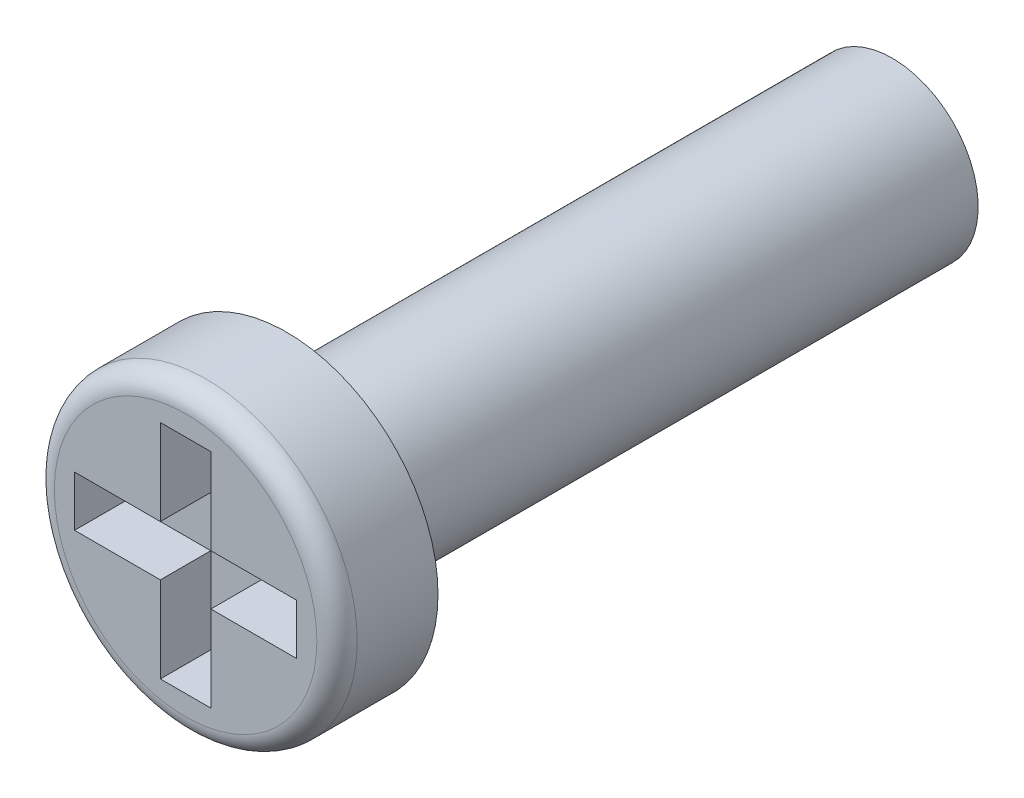
SolidWorks part; units mm, degrees
ref_plane "Front Plane" through (0, 0, 0) normal (0, 0, 1) x (1, 0, 0)
ref_plane "Top Plane" through (0, 0, 0) normal (0, 1, 0) x (1, 0, 0)
ref_plane "Right Plane" through (0, 0, 0) normal (1, 0, 0) x (0, 0, -1)
sketch "Sketch1" plane through (0, 0, 0) normal (0, 0, 1) x (1, 0, 0)
  circle A0 centre (0, 0) radius 1.5
  dimension "D1" = 3
extrude "Boss-Extrude1" add sketch "Sketch1" along normal blind 1
sketch "Sketch2" plane through (0, 0, 0) normal (0, 0, -1) x (-1, 0, 0)
  circle A0 centre (0, 0) radius 0.85
  dimension "D1" = 1.7
extrude "Boss-Extrude2" add sketch "Sketch2" along normal blind 6
sketch "Sketch3" plane through (0, 0, 1) normal (0, 0, 1) x (1, 0, 0)
  line L0 (-0.25, 1.1) -> (-0.25, 0.25)
  line L1 (-0.25, 1.1) -> (0.25, 1.1)
  line L3 (-0.25, -1.1) -> (0.25, -1.1)
  line L5 (0, -1.1) -> (0, 1.1) construction
  line L6 (-0.25, 0) -> (0.25, 0) construction
  line L8 (-1.1, 0.25) -> (-1.1, -0.25)
  line L10 (1.1, 0.25) -> (1.1, -0.25)
  line L11 (0, -0.25) -> (0, 0.25) construction
  line L12 (-1.1, 0) -> (1.1, 0) construction
  line L13 (-0.25, -1.1) -> (-0.25, -0.25)
  line L14 (0.25, 1.1) -> (0.25, 0.25)
  line L15 (0.25, -1.1) -> (0.25, -0.25)
  line L16 (-1.1, 0.25) -> (-0.25, 0.25)
  line L17 (0.25, 0.25) -> (1.1, 0.25)
  line L18 (-1.1, -0.25) -> (-0.25, -0.25)
  line L19 (0.25, -0.25) -> (1.1, -0.25)
  point P0 (0, 0)
  point P4 (0, 0)
  dimension "D1" = 2.2
  dimension "D2" = 0.5
  dimension "D3" = 0.5
  dimension "D4" = 2.2
extrude "Cut-Extrude1" cut sketch "Sketch3" against normal blind 0.5
fillet "Fillet1" radius 0.2 1 edges at (1.5, 0, 1)
